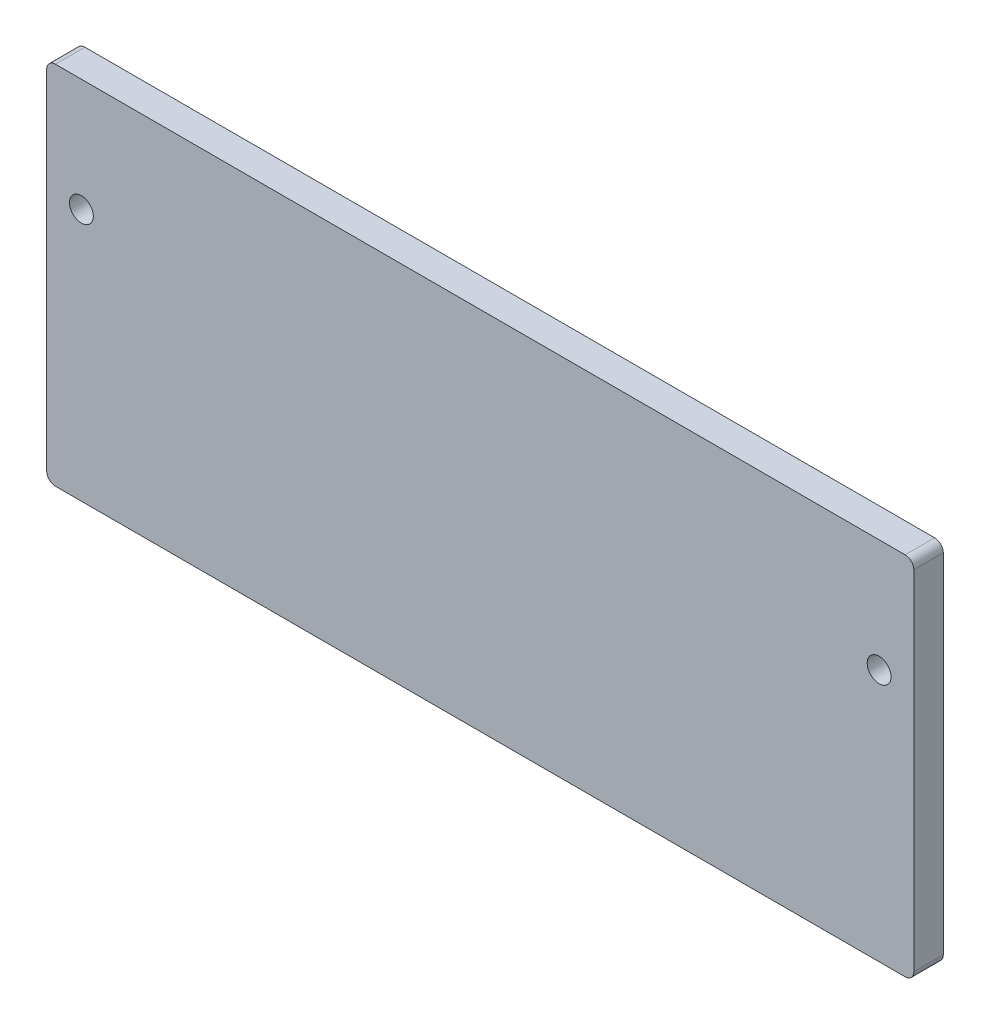
SolidWorks part; units mm, degrees
ref_plane "Front Plane" through (0, 0, 0) normal (0, 0, 1) x (1, 0, 0)
ref_plane "Top Plane" through (0, 0, 0) normal (0, 1, 0) x (1, 0, 0)
ref_plane "Right Plane" through (0, 0, 0) normal (1, 0, 0) x (0, 0, -1)
sketch "Sketch1" plane through (0, 0, 0) normal (0, 0, 1) x (1, 0, 0)
  line L1 (100, -42.15) -> (-100, -42.15)
  line L2 (100, -42.15) -> (100, 42.15)
  line L3 (100, 42.15) -> (-100, 42.15)
  line L4 (-100, -42.15) -> (-100, 42.15)
  line L5 (100, -42.15) -> (-100, 42.15) construction
  line L6 (100, 42.15) -> (-100, -42.15) construction
  point P0 (0, 0)
  dimension "D1" = 200
  dimension "D2" = 84.3
extrude "Boss-Extrude1" add sketch "Sketch1" along normal blind 6.8
sketch "Sketch2" plane through (0, 0, 6.8) normal (0, 0, 1) x (1, 0, 0)
  line L0 (100, 42.15) -> (-100, 42.15) construction
  line L1 (92, 16.15) -> (-92, 16.15) construction
  circle A0 centre (-92, 16.15) radius 2.75
  circle A1 centre (92, 16.15) radius 2.75
  point P10 (0, 16.15)
  dimension "D1" = 5.5
  dimension "D2" = 92
  dimension "D3" = 26
extrude "Cut-Extrude1" cut sketch "Sketch2" against normal blind 6.8
fillet "Fillet1" radius 2 4 edges at (100, 42.15, 3.4) (100, -42.15, 3.4) (-100, -42.15, 3.4) (-100, 42.15, 3.4)
sketch "Sketch3" plane through (0, 0, 0) normal (0, 0, -1) x (-1, 0, 0)
  line L0 (-71.5, -15.65) -> (-41.5, -15.65) construction
  line L1 (-100, -40.15) -> (-100, 40.15) construction
  line L2 (-48, -22.15) -> (-65, -22.15)
  line L3 (-48, -22.15) -> (-48, -9.15)
  line L4 (-48, -9.15) -> (-65, -9.15)
  line L5 (-65, -22.15) -> (-65, -9.15)
  line L6 (-48, -22.15) -> (-65, -9.15) construction
  line L7 (-48, -9.15) -> (-65, -22.15) construction
  line L8 (98, -42.15) -> (-98, -42.15) construction
  circle A0 centre (-71.5, -15.65) radius 1.75
  circle A1 centre (-41.5, -15.65) radius 1.75
  point P4 (-56.5, -15.65)
  dimension "D2" = 3.5
  dimension "D1" = 30
  dimension "D3" = 17
  dimension "D4" = 13
  dimension "D5" = 35
  dimension "D6" = 20
extrude "Cut-Extrude2" [suppressed] cut sketch "Sketch3" against normal through all
fillet "Fillet2" [suppressed] radius 1
sketch "Sketch4" [suppressed] plane through (0, 0, 6.8) normal (0, 0, 1) x (1, 0, 0)
  line L0 (40, 15) -> (40, 0) construction
  line L1 (46, -6.5) -> (34, -6.5)
  line L2 (46, -6.5) -> (46, 6.5)
  line L3 (46, 6.5) -> (34, 6.5)
  line L4 (34, -6.5) -> (34, 6.5)
  line L5 (46, -6.5) -> (34, 6.5) construction
  line L6 (46, 6.5) -> (34, -6.5) construction
  line L7 (40, 0) -> (40, -15) construction
  circle A0 centre (40, 15) radius 1.75
  circle A1 centre (40, -15) radius 1.75
  point P0 (40, 0)
  dimension "D1" = 3.5
  dimension "D2" = 30
  dimension "D3" = 13
  dimension "D4" = 12
  dimension "D5" = 40
extrude "Cut-Extrude3" [suppressed] cut sketch "Sketch4" against normal blind 10
fillet "Fillet3" [suppressed] radius 1
